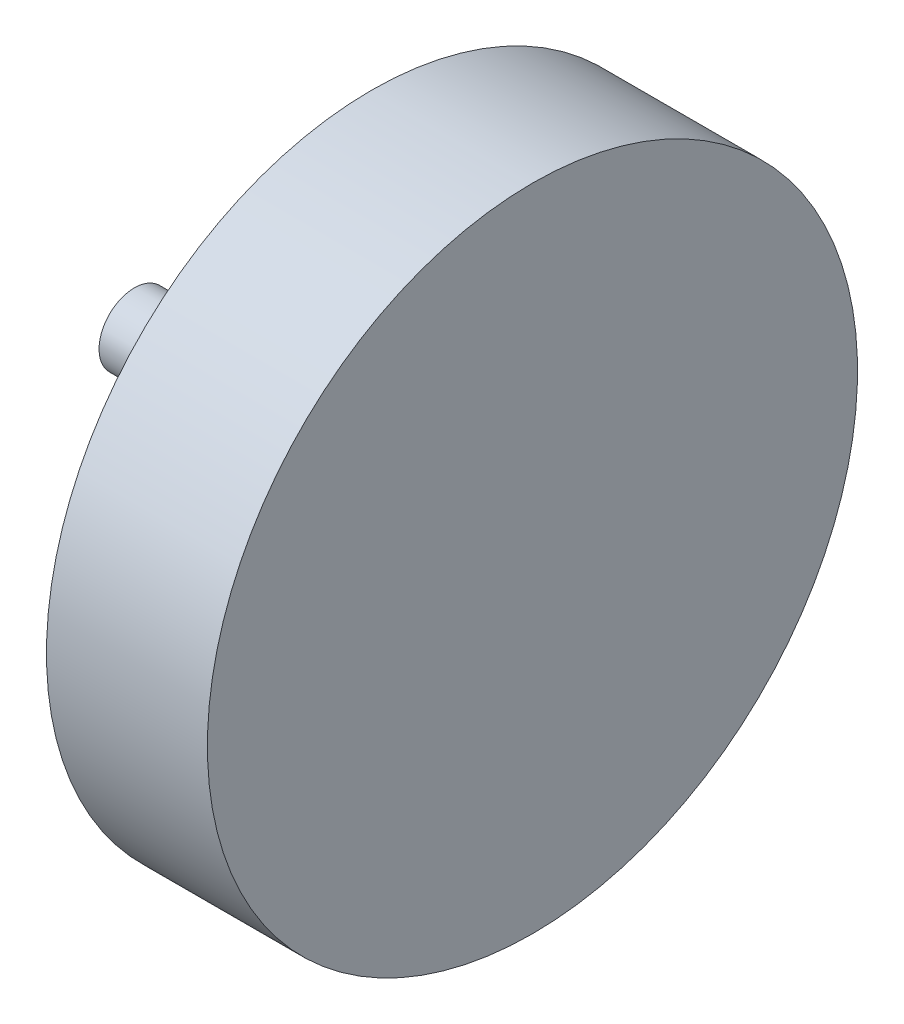
SolidWorks part; units mm, degrees
ref_plane "Front Plane" through (0, 0, 0) normal (0, 0, 1) x (1, 0, 0)
ref_plane "Top Plane" through (0, 0, 0) normal (0, 1, 0) x (1, 0, 0)
ref_plane "Right Plane" through (0, 0, 0) normal (1, 0, 0) x (0, 0, -1)
sketch "Sketch1" plane through (0, 0, 0) normal (0, 0, 1) x (1, 0, 0)
  line L0 (72.797, 15.24) -> (85.497, 15.24)
  line L1 (85.497, 15.24) -> (187.097, 42.4636)
  line L2 (0, 0) -> (0, 27.94)
  line L3 (0, 27.94) -> (50.8, 27.94)
  line L4 (50.8, 27.94) -> (72.797, 15.24)
  line L5 (187.097, 42.4636) -> (187.097, 256.54)
  line L6 (187.097, 256.54) -> (314.097, 256.54)
  line L7 (314.097, 256.54) -> (314.097, 0)
  line L8 (314.097, 0) -> (0, 0)
  dimension "D1" = 27.94
  dimension "D2" = 50.8
  dimension "D3" = 150
  dimension "D4" = 12.7
  dimension "D5" = 12.7
  dimension "D6" = 165
  dimension "D7" = 101.6
  dimension "D8" = 256.54
  dimension "D9" = 127
revolve "Revolve2" add sketch "Sketch1" angle 360 about L8
